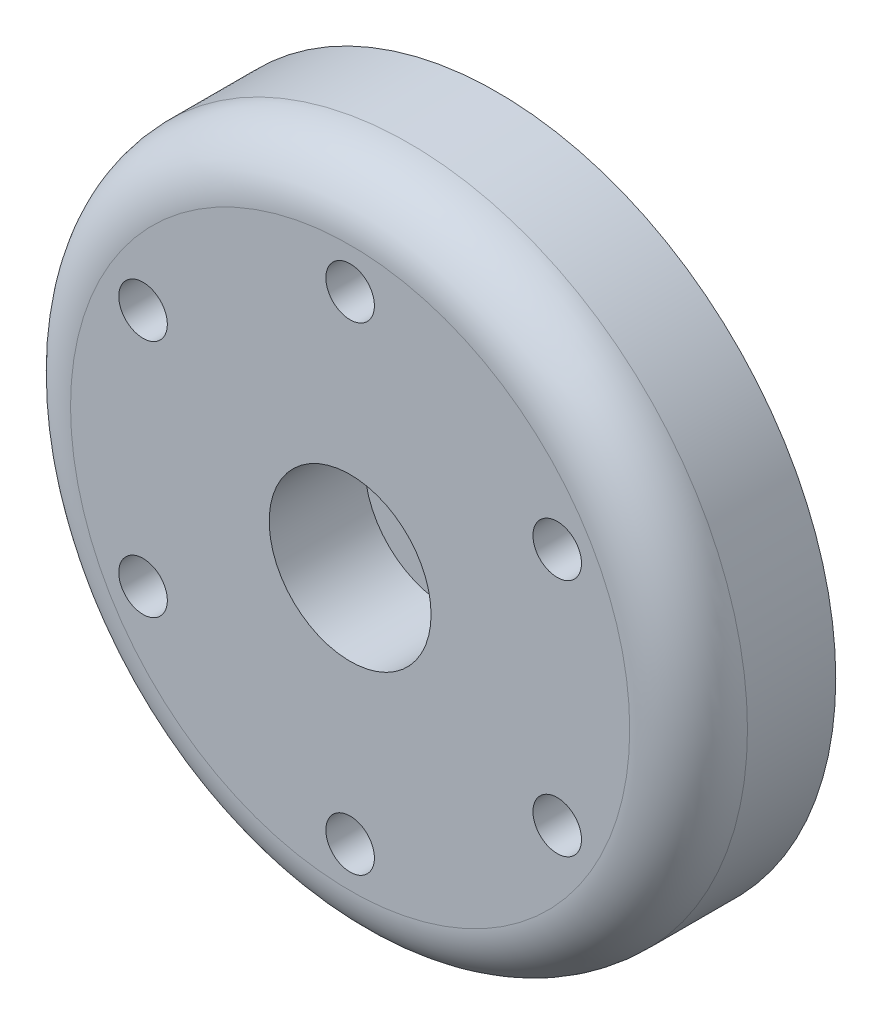
SolidWorks part; units mm, degrees
material "6061 Alloy"
ref_plane "Front" through (0, 0, 0) normal (0, 0, 1) x (1, 0, 0)
ref_plane "Top" through (0, 0, 0) normal (0, 1, 0) x (1, 0, 0)
ref_plane "Right" through (0, 0, 0) normal (1, 0, 0) x (0, 0, -1)
ref_plane "Plane1" through (0, 0, 0) normal (0, -1, 0) x (1, 0, 0)
sketch "Sketch1" plane through (0, 0, 0) normal (0, -1, 0) x (1, 0, 0)
  line L0 (23, 10) -> (0, 10)
  line L1 (0, 10) -> (0, 0)
  line L2 (0, 0) -> (23, 0)
  line L3 (23, 0) -> (23, 10)
  line L4 (0, 10) -> (0, 0) construction
revolve "Revolve1" add sketch "Sketch1" angle 360 about L4
hole_wizard "Hole1" positions "Sketch3" profile "Sketch2" legacy
sketch "Sketch3" plane through (0, 0, 0) normal (0, 0, -1) x (-1, 0, 0)
  point P0 (0, 0)
sketch "Sketch2" plane through (0, 0, 0) normal (1, 0, 0) x (0, 1, 0)
  line L0 (0, 0) -> (0, 5.8)
  line L1 (0, 5.8) -> (20, 5.8)
  line L2 (20, 5.8) -> (20, 0)
  line L3 (20, 0) -> (0, 0)
  line L4 (0, 110) -> (0, -10) construction
  dimension "Diameter" = 40
  dimension "Depth" = 5.8
sketch "Sketch4" plane through (0, 0, 0) normal (0, -1, 0) x (1, 0, 0)
  line L0 (12.5, 5.8) -> (0, 5.8)
  line L1 (0, 5.8) -> (0, 0)
  line L2 (0, 0) -> (12.5, 0)
  line L3 (12.5, 0) -> (12.5, 5.8)
  line L4 (0, 5.8) -> (0, 0) construction
revolve "Revolve2" add sketch "Sketch4" angle 360 about L4
hole_wizard "M4x0.7 Tapped Hole1" positions "Sketch6" profile "Sketch5" tap size "M4x0.7" standard "ANSI Metric" end condition through all
sketch "Sketch6" plane through (0, 0, 5.8) normal (0, 0, -1) x (-1, 0, 0)
  point P0 (-14.0729, 8.125)
  point P1 (-14.0729, -8.125)
  point P2 (0, -16.25)
  point P3 (14.0729, -8.125)
  point P4 (14.0729, 8.125)
  point P5 (0, 16.25)
sketch "Sketch5" plane through (14.0729, 8.125, 5.8) normal (1, 0, 0) x (0, 1, 0)
  line L0 (0, 0) -> (0, 4.2)
  line L1 (0, 4.2) -> (1.65, 4.2)
  line L2 (1.65, 4.2) -> (1.65, 0)
  line L5 (1.65, 0) -> (0, 0)
  line L11 (0, -6.35) -> (0, 107.95) construction
  dimension "Thru Tap Drill Dia." = 3.3
  dimension "Thru Tap Drill Depth" = 4.2
hole_wizard "CBORE for M6 SHCS1" positions "Sketch8" profile "Sketch7" counterbore size "M6" standard "ANSI Metric" end condition through all
sketch "Sketch8" plane through (0, 0, 10) normal (0, 0, 1) x (1, 0, 0)
  point P0 (0, 0)
sketch "Sketch7" plane through (0, 0, 10) normal (1, 0, 0) x (0, -1, 0)
  line L0 (0, 0) -> (0, 10)
  line L1 (0, 10) -> (3.5, 10)
  line L3 (3.5, 10) -> (3.5, 6.5)
  line L4 (3.5, 6.5) -> (5.5, 6.5)
  line L5 (5.5, 6.5) -> (5.5, 0)
  line L7 (5.5, 0) -> (0, 0)
  line L11 (0, -6.35) -> (0, 107.95) construction
  dimension "Thru Hole Dia." = 7
  dimension "Thru Hole Depth" = 10
  dimension "C'Bore Dia." = 11
  dimension "C'Bore Depth" = 6.5
fillet "Fillet1" radius 4 1 edges at (-23, 0, 10)
